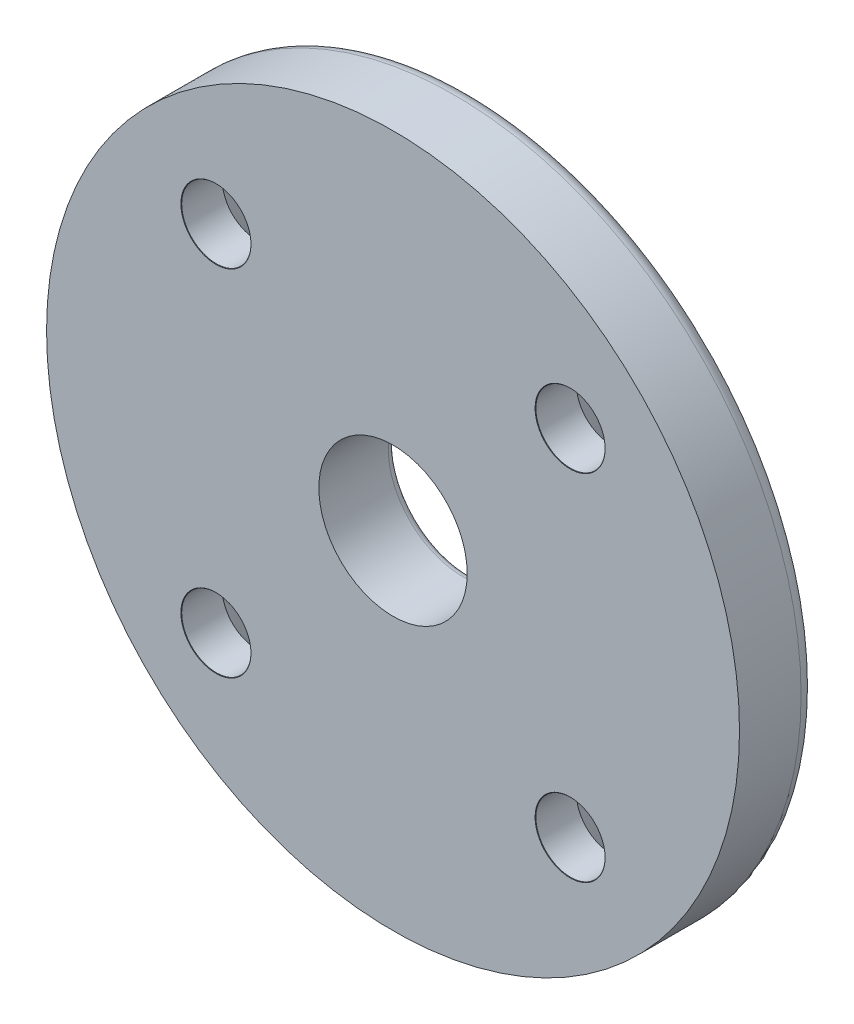
SolidWorks part; units mm, degrees
material "3.3547 (EN-AW 5083)"
ref_plane "Ebene vorne" through (0, 0, 0) normal (0, 0, 1) x (1, 0, 0)
ref_plane "Ebene oben" through (0, 0, 0) normal (0, 1, 0) x (1, 0, 0)
ref_plane "Ebene rechts" through (0, 0, 0) normal (1, 0, 0) x (0, 0, -1)
sketch "Skizze1" plane through (0, 0, 0) normal (0, 0, 1) x (1, 0, 0)
  line L1 (-11.5, 11.5) -> (11.5, 11.5) construction
  line L2 (-11.5, 11.5) -> (-11.5, -11.5) construction
  line L3 (-11.5, -11.5) -> (11.5, -11.5) construction
  line L4 (11.5, 11.5) -> (11.5, -11.5) construction
  line L5 (0, -11.5) -> (0, 11.5) construction
  line L6 (-11.5, 0) -> (11.5, 0) construction
  circle A0 centre (0, 0) radius 22.5
  circle A1 centre (0, 0) radius 4.8185
  circle A2 centre (-11.5, 11.5) radius 2
  circle A3 centre (11.5, 11.5) radius 2
  circle A4 centre (-11.5, -11.5) radius 2
  circle A5 centre (11.5, -11.5) radius 2
  dimension "D1" = 23
  dimension "D2" = 23
extrude "Aufsatz-Linear austragen1" add sketch "Skizze1" along normal blind 5
fillet "Verrundung1" radius 1 1 edges at (22.5, 0, 0)
fillet "Verrundung2" radius 0.5 1 edges at (4.8185, 0, 0)
hole_wizard "Formsenkung für M4 Senkschraube mit Innensechskant1" positions "3D-Skizze1" profile "Skizze2" countersink size "M4" standard "DIN" end condition through all
sketch3d "3D-Skizze1"
  line L0 (11.5, 11.5, 5) -> (11.5, 11.5, 0) construction
  line L1 (-11.5, 11.5, 5) -> (-11.5, 11.5, 0) construction
  line L2 (11.5, -11.5, 5) -> (11.5, -11.5, 0) construction
  line L3 (-11.5, -11.5, 5) -> (-11.5, -11.5, 0) construction
  point P0 (11.5, 11.5, 0)
  point P4 (-11.5, 11.5, 0)
  point P8 (11.5, -11.5, 0)
  point P12 (-11.5, -11.5, 0)
sketch "Skizze2" plane through (11.5, 11.5, 0) normal (1, 0, 0) x (0, 1, 0)
  line L0 (0, 0) -> (0, 5)
  line L1 (0, 5) -> (2.275, 5)
  line L2 (2.25, 4.975) -> (2.25, 2.34)
  line L3 (2.25, 2.34) -> (4.59, 0)
  line L5 (4.59, 0) -> (0, 0)
  line L6 (-2.25, 2.34) -> (-4.59, 0) construction
  line L7 (2.275, 5) -> (2.25, 4.975)
  line L8 (-2.275, 5) -> (-2.25, 4.975) construction
  line L11 (0, -6.35) -> (0, 107.95) construction
  dimension "Bohrerdurchmesser" = 4.5
  dimension "Bohrungstiefe" = 5
  dimension "Senkdurchmesser (Oben)" = 9.18
  dimension "Senkwinkel (Oben)" = 90
  dimension "Senkdurchmesser (Unten)" = 4.55
  dimension "Senkwinkel (Unten)" = 90
